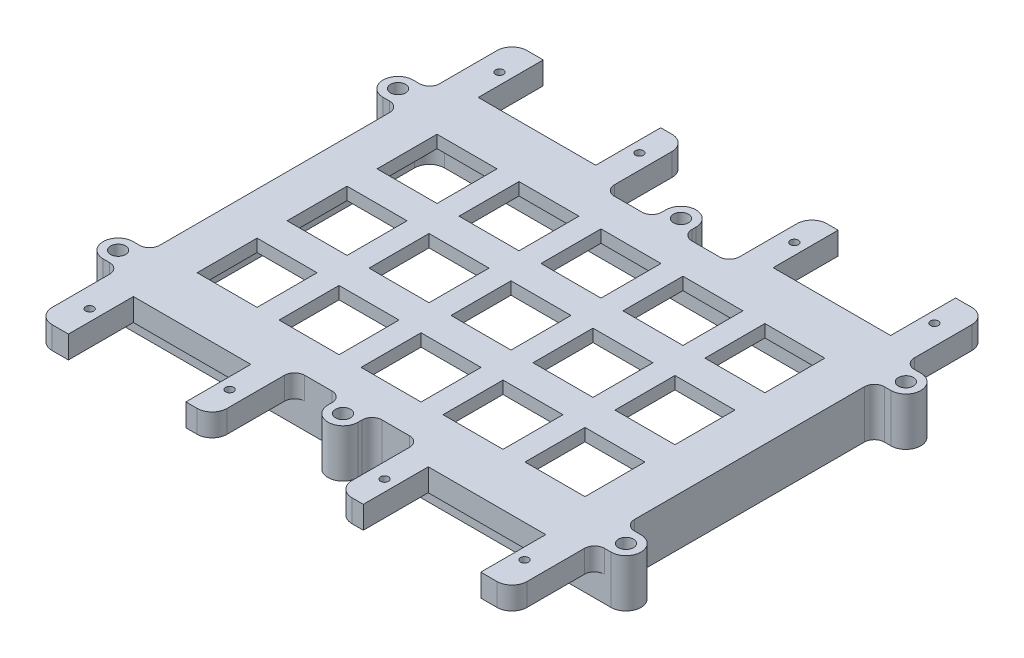
SolidWorks part; units mm, degrees
ref_plane "前视基准面" through (0, 0, 0) normal (0, 0, 1) x (1, 0, 0)
ref_plane "上视基准面" through (0, 0, 0) normal (0, 1, 0) x (1, 0, 0)
ref_plane "右视基准面" through (0, 0, 0) normal (1, 0, 0) x (0, 0, -1)
other "Configuration Table"
sketch "草图1" plane through (0, 0, 0) normal (0, 1, 0) x (1, 0, 0)
  line L0 (0, 35.4779) -> (0, -35.3561) construction
  line L2 (-47.5, 23) -> (-47.5, -23)
  line L4 (47.5, 23) -> (47.5, -23)
  line L5 (-47.5, 31) -> (47.5, -31) construction
  line L6 (-47.5, -31) -> (47.5, 31) construction
  line L15 (-78.7463, 0) -> (58.6748, 0) construction
  line L24 (-10.5, 31) -> (-5, 31)
  line L27 (-10.5, -31) -> (-5, -31)
  line L28 (49.5, 31) -> (50.8, 31)
  line L29 (-49.5, 31) -> (-50.8, 31)
  line L31 (-49.5, 25) -> (-50.8, 25)
  line L33 (49.5, 25) -> (50.8, 25)
  line L36 (49.5, -25) -> (50.8, -25)
  line L37 (49.5, -31) -> (50.8, -31)
  line L38 (-49.5, -31) -> (-50.8, -31)
  line L39 (-49.5, -25) -> (-50.8, -25)
  line L41 (-3, -33.8) -> (-3, -33)
  line L43 (-3, 33.8) -> (-3, 33)
  line L45 (3, 33.8) -> (3, 33)
  line L47 (3, -33.8) -> (3, -33)
  line L48 (5, 31) -> (10.5, 31)
  line L49 (5, -31) -> (10.5, -31)
  line L54 (29.5, 63.8424) -> (29.5, 47.5) construction
  line L56 (47.5, 33) -> (47.5, 44.5)
  line L57 (44.5, 47.5) -> (41.25, 47.5)
  line L58 (12.5, 33) -> (12.5, 44.5)
  line L59 (17.75, 47.5) -> (15.5, 47.5)
  line L60 (17.75, 34.5) -> (41.25, 34.5)
  line L61 (17.75, 34.5) -> (17.75, 47.5)
  line L63 (41.25, 34.5) -> (41.25, 47.5)
  line L65 (12.5, -33) -> (12.5, -44.5)
  line L66 (29.5, 34.5) -> (29.5, 25) construction
  line L67 (17.75, -47.5) -> (15.5, -47.5)
  line L68 (17.75, -34.5) -> (17.75, -47.5)
  line L69 (17.75, -34.5) -> (41.25, -34.5)
  line L70 (41.25, -34.5) -> (41.25, -47.5)
  line L71 (44.5, -47.5) -> (41.25, -47.5)
  line L72 (47.5, -33) -> (47.5, -44.5)
  line L73 (-47.5, -33) -> (-47.5, -44.5)
  line L74 (-44.5, -47.5) -> (-41.25, -47.5)
  line L75 (-41.25, -34.5) -> (-41.25, -47.5)
  line L76 (-17.75, -34.5) -> (-41.25, -34.5)
  line L77 (-17.75, -34.5) -> (-17.75, -47.5)
  line L78 (-17.75, -47.5) -> (-15.5, -47.5)
  line L79 (-12.5, -33) -> (-12.5, -44.5)
  line L82 (-12.5, 33) -> (-12.5, 44.5)
  line L83 (-17.75, 47.5) -> (-15.5, 47.5)
  line L84 (-17.75, 34.5) -> (-17.75, 47.5)
  line L85 (-17.75, 34.5) -> (-41.25, 34.5)
  line L86 (-41.25, 34.5) -> (-41.25, 47.5)
  line L87 (-44.5, 47.5) -> (-41.25, 47.5)
  line L88 (-47.5, 33) -> (-47.5, 44.5)
  arc A4 (-50.8, 31) -> (-50.8, 25) centre (-50.8, 28) ccw
  circle A5 centre (-50.8, 28) radius 1.5
  circle A6 centre (50.8, 28) radius 1.5
  arc A7 (50.8, 31) -> (50.8, 25) centre (50.8, 28) cw
  circle A8 centre (50.8, -28) radius 1.5
  arc A9 (50.8, -31) -> (50.8, -25) centre (50.8, -28) ccw
  circle A10 centre (-50.8, -28) radius 1.5
  arc A11 (-50.8, -31) -> (-50.8, -25) centre (-50.8, -28) cw
  arc A12 (-3, 33.8) -> (3, 33.8) centre (0, 33.8) cw
  circle A13 centre (0, 33.8) radius 1.5
  circle A14 centre (0, -33.8) radius 1.5
  arc A15 (-3, -33.8) -> (3, -33.8) centre (0, -33.8) ccw
  arc A16 (47.5, 44.5) -> (44.5, 47.5) centre (44.5, 44.5) ccw
  arc A17 (15.5, 47.5) -> (12.5, 44.5) centre (15.5, 44.5) ccw
  circle A18 centre (43.5, 41) radius 0.8
  circle A19 centre (15.5, 41) radius 0.8
  circle A20 centre (43.5, -41) radius 0.8
  circle A21 centre (15.5, -41) radius 0.8
  arc A22 (15.5, -47.5) -> (12.5, -44.5) centre (15.5, -44.5) cw
  arc A23 (47.5, -44.5) -> (44.5, -47.5) centre (44.5, -44.5) cw
  circle A24 centre (-15.5, -41) radius 0.8
  circle A25 centre (-43.5, -41) radius 0.8
  arc A26 (-47.5, -44.5) -> (-44.5, -47.5) centre (-44.5, -44.5) ccw
  arc A27 (-15.5, -47.5) -> (-12.5, -44.5) centre (-15.5, -44.5) ccw
  circle A28 centre (-43.5, 41) radius 0.8
  circle A29 centre (-15.5, 41) radius 0.8
  arc A30 (-15.5, 47.5) -> (-12.5, 44.5) centre (-15.5, 44.5) cw
  arc A31 (-47.5, 44.5) -> (-44.5, 47.5) centre (-44.5, 44.5) cw
  arc A32 (47.5, -23) -> (49.5, -25) centre (49.5, -23) ccw
  arc A33 (49.5, 25) -> (47.5, 23) centre (49.5, 23) ccw
  arc A34 (-49.5, -25) -> (-47.5, -23) centre (-49.5, -23) ccw
  arc A35 (-47.5, 23) -> (-49.5, 25) centre (-49.5, 23) ccw
  arc A36 (-49.5, -31) -> (-47.5, -33) centre (-49.5, -33) cw
  arc A37 (-12.5, -33) -> (-10.5, -31) centre (-10.5, -33) cw
  arc A38 (-3, -33) -> (-5, -31) centre (-5, -33) ccw
  arc A39 (5, -31) -> (3, -33) centre (5, -33) ccw
  arc A40 (10.5, -31) -> (12.5, -33) centre (10.5, -33) cw
  arc A41 (47.5, -33) -> (49.5, -31) centre (49.5, -33) cw
  arc A42 (47.5, 33) -> (49.5, 31) centre (49.5, 33) ccw
  arc A43 (10.5, 31) -> (12.5, 33) centre (10.5, 33) ccw
  arc A44 (5, 31) -> (3, 33) centre (5, 33) cw
  arc A45 (-3, 33) -> (-5, 31) centre (-5, 33) cw
  arc A46 (-10.5, 31) -> (-12.5, 33) centre (-10.5, 33) cw
  arc A47 (-47.5, 33) -> (-49.5, 31) centre (-49.5, 33) cw
  point P0 (0, 0)
  point P14 (47.5, -25)
  point P21 (29.5, 41)
  point P24 (47.5, 25)
  point P62 (47.5, 47.5)
  point P65 (12.5, 47.5)
  point P117 (-47.5, -25)
  point P120 (-47.5, 25)
  point P126 (-12.5, -31)
  point P129 (-3, -31)
  point P132 (3, -31)
  point P135 (12.5, -31)
  point P144 (12.5, 31)
  point P147 (3, 31)
  point P150 (-3, 31)
  point P153 (-12.5, 31)
  dimension "D8" = 2.8
  dimension "D11" = 3
  dimension "D12" = 6.5
  dimension "D3" = 2
  dimension "D1" = 95
  dimension "D2" = 62
  dimension "D4" = 35
  dimension "D5" = 23.5
  dimension "D6" = 3.3
  dimension "D7" = 6
  dimension "D9" = 6
  dimension "D13" = 2.25
extrude "凸台-拉伸1" add sketch "草图1" against normal blind 9.6
sketch "草图2" plane through (0, -9.6, 0) normal (0, -1, 0) x (1, 0, 0)
  line L0 (-63.1336, 0) -> (63.5579, 0) construction
  line L5 (0, 56.9992) -> (0, 48.5806) construction
  line L18 (3, 33.8) -> (3, 33) construction
  line L19 (63.5579, 31) -> (5, 31)
  line L20 (63.5579, 31) -> (63.5579, 53.6942)
  line L21 (63.5579, 53.6942) -> (-73.0103, 53.6942)
  line L22 (-73.0103, 31) -> (-73.0103, 53.6942)
  line L23 (-3, 33) -> (-3, 33.8) construction
  line L24 (3, 33.8) -> (3, 33)
  line L25 (-3, 33) -> (-3, 33.8)
  line L26 (-5, 31) -> (-73.0103, 31)
  line L27 (63.5579, -31) -> (63.5579, -53.6942)
  line L28 (63.5579, -53.6942) -> (-73.0103, -53.6942)
  line L29 (-73.0103, -31) -> (-73.0103, -53.6942)
  line L30 (-5, -31) -> (-73.0103, -31)
  line L31 (-3, -33) -> (-3, -33.8)
  line L32 (3, -33.8) -> (3, -33)
  line L33 (63.5579, -31) -> (5, -31)
  arc A3 (3, 33) -> (5, 31) centre (5, 33) ccw construction
  arc A4 (3, 33.8) -> (-3, 33.8) centre (0, 33.8) ccw construction
  arc A5 (-5, 31) -> (-3, 33) centre (-5, 33) ccw construction
  arc A6 (3, 33) -> (5, 31) centre (5, 33) ccw
  arc A7 (3, 33.8) -> (-3, 33.8) centre (0, 33.8) ccw
  arc A8 (-5, 31) -> (-3, 33) centre (-5, 33) ccw
  arc A9 (-5, -31) -> (-3, -33) centre (-5, -33) cw
  arc A10 (3, -33.8) -> (-3, -33.8) centre (0, -33.8) cw
  arc A11 (3, -33) -> (5, -31) centre (5, -33) cw
extrude "切除-拉伸1" cut sketch "草图2" against normal blind 5.1
sketch "草图3" plane through (0, -9.6, 0) normal (0, -1, 0) x (1, 0, 0)
  line L0 (47.5, 23) -> (47.5, -23) construction
  line L1 (-45, -28.5) -> (45, -28.5)
  line L2 (-45, -28.5) -> (-45, 28.5)
  line L3 (-45, 28.5) -> (45, 28.5)
  line L4 (45, -28.5) -> (45, 28.5)
  line L5 (-45, -28.5) -> (45, 28.5) construction
  line L6 (-45, 28.5) -> (45, -28.5) construction
  line L7 (-50.8, 31) -> (-5, 31) construction
  point P0 (0, 0)
  dimension "D1" = 2.5
  dimension "D2" = 2.5
extrude "切除-拉伸2" cut sketch "草图3" against normal blind 7.1
fillet "圆角1" radius 3 4 edges at (-45, -6.05, -28.5) (-45, -6.05, 28.5) (45, -6.05, -28.5) (45, -6.05, 28.5)
sketch "草图11" plane through (0, -2.5, 0) normal (0, -1, 0) x (1, 0, 0)
  line L0 (0, 44.5522) -> (0, -50.2123) construction
  line L1 (-64.7486, 0) -> (58.5739, 0) construction
  line L2 (42, 28.5) -> (-42, 28.5) construction
  line L3 (-30, 17) -> (30, 17)
  line L4 (-30, 17) -> (-30, 19.5)
  line L5 (-30, 19.5) -> (-1.5, 19.5)
  line L6 (30, 17) -> (30, 19.5)
  line L7 (-30, 17) -> (30, 19.5) construction
  line L8 (-30, 19.5) -> (30, 17) construction
  line L9 (1.5, 19.5) -> (30, 19.5)
  line L10 (-1.5, 28.5) -> (1.5, 28.5)
  line L11 (-1.5, 28.5) -> (-1.5, 19.5)
  line L13 (1.5, 28.5) -> (1.5, 19.5)
  line L14 (1.5, -28.5) -> (1.5, -19.5)
  line L15 (-1.5, -28.5) -> (1.5, -28.5)
  line L16 (-1.5, -28.5) -> (-1.5, -19.5)
  line L17 (-30, -19.5) -> (-1.5, -19.5)
  line L18 (-30, -17) -> (-30, -19.5)
  line L19 (-30, -17) -> (30, -17)
  line L20 (30, -17) -> (30, -19.5)
  line L21 (1.5, -19.5) -> (30, -19.5)
  point P5 (0, 18.25)
  dimension "D1" = 60
  dimension "D2" = 2.5
  dimension "D3" = 9
  dimension "D4" = 3
extrude "凸台-拉伸2" [suppressed] add sketch "草图11" along normal blind 2
sketch "草图12" plane through (0, -2.5, 0) normal (0, -1, 0) x (1, 0, 0)
  line L0 (0, 44.2091) -> (0, -42.6655) construction
  line L1 (-42, 25.5) -> (-7, 25.5)
  line L2 (-42, 25.5) -> (-42, 23)
  line L3 (-42, 23) -> (-7, 23)
  line L4 (-7, 25.5) -> (-7, 23)
  line L5 (-53.0853, 0) -> (71.5236, 0) construction
  line L6 (42, 23) -> (7, 23)
  line L7 (7, 25.5) -> (7, 23)
  line L8 (42, 25.5) -> (7, 25.5)
  line L9 (42, 25.5) -> (42, 23)
  line L10 (42, -25.5) -> (42, -23)
  line L11 (42, -25.5) -> (7, -25.5)
  line L12 (7, -25.5) -> (7, -23)
  line L13 (42, -23) -> (7, -23)
  line L14 (-42, -23) -> (-7, -23)
  line L15 (-7, -25.5) -> (-7, -23)
  line L16 (-42, -25.5) -> (-7, -25.5)
  line L17 (-42, -25.5) -> (-42, -23)
  dimension "D1" = 35
  dimension "D2" = 2.5
fillet "圆角2" radius 1 8 edges at (0, -2.5, -28.5) (-44.1213, -2.5, -27.6213) (-45, -2.5, 0) (-44.1213, -2.5, 27.6213) (0, -2.5, 28.5) (44.1213, -2.5, 27.6213) (45, -2.5, 0) (44.1213, -2.5, -27.6213)
sketch "草图13" plane through (0, -2.5, 0) normal (0, -1, 0) x (1, 0, 0)
  line L0 (-56.0869, 0) -> (61.3182, 0) construction
  line L1 (0, 42.7512) -> (0, -42.4082) construction
  line L2 (-45, -25.5) -> (-45, 25.5) construction
  line L3 (-39, 24) -> (-27, 24)
  line L4 (-39, 24) -> (-39, 12)
  line L5 (-39, 12) -> (-27, 12)
  line L6 (-27, 24) -> (-27, 12)
  line L7 (-39, 24) -> (-27, 12) construction
  line L8 (-39, 12) -> (-27, 24) construction
  line L9 (-22.6, 24) -> (-22.6, 12)
  line L10 (-22.6, 24) -> (-10.6, 24)
  line L11 (-10.6, 24) -> (-10.6, 12)
  line L12 (-22.6, 12) -> (-10.6, 12)
  line L13 (-6.2, 24) -> (-6.2, 12)
  line L14 (-6.2, 24) -> (5.8, 24)
  line L15 (5.8, 24) -> (5.8, 12)
  line L16 (-6.2, 12) -> (5.8, 12)
  line L17 (10.2, 24) -> (10.2, 12)
  line L18 (10.2, 24) -> (22.2, 24)
  line L19 (22.2, 24) -> (22.2, 12)
  line L20 (10.2, 12) -> (22.2, 12)
  line L21 (26.6, 24) -> (26.6, 12)
  line L22 (26.6, 24) -> (38.6, 24)
  line L23 (38.6, 24) -> (38.6, 12)
  line L24 (26.6, 12) -> (38.6, 12)
  line L25 (-22.6, 6) -> (-22.6, -6)
  line L26 (-22.6, 6) -> (-10.6, 6)
  line L27 (-10.6, 6) -> (-10.6, -6)
  line L28 (-22.6, -6) -> (-10.6, -6)
  line L29 (-6.2, 6) -> (-6.2, -6)
  line L30 (-6.2, 6) -> (5.8, 6)
  line L31 (5.8, 6) -> (5.8, -6)
  line L32 (-6.2, -6) -> (5.8, -6)
  line L33 (10.2, 6) -> (10.2, -6)
  line L34 (10.2, 6) -> (22.2, 6)
  line L35 (22.2, 6) -> (22.2, -6)
  line L36 (10.2, -6) -> (22.2, -6)
  line L37 (26.6, 6) -> (26.6, -6)
  line L38 (26.6, 6) -> (38.6, 6)
  line L39 (38.6, 6) -> (38.6, -6)
  line L40 (26.6, -6) -> (38.6, -6)
  line L41 (-22.6, -12) -> (-22.6, -24)
  line L42 (-22.6, -12) -> (-10.6, -12)
  line L43 (-10.6, -12) -> (-10.6, -24)
  line L44 (-22.6, -24) -> (-10.6, -24)
  line L45 (-6.2, -12) -> (-6.2, -24)
  line L46 (-6.2, -12) -> (5.8, -12)
  line L47 (5.8, -12) -> (5.8, -24)
  line L48 (-6.2, -24) -> (5.8, -24)
  line L49 (10.2, -12) -> (10.2, -24)
  line L50 (10.2, -12) -> (22.2, -12)
  line L51 (22.2, -12) -> (22.2, -24)
  line L52 (10.2, -24) -> (22.2, -24)
  line L53 (26.6, -12) -> (26.6, -24)
  line L54 (26.6, -12) -> (38.6, -12)
  line L55 (38.6, -12) -> (38.6, -24)
  line L56 (26.6, -24) -> (38.6, -24)
  line L57 (-39, 6) -> (-39, -6)
  line L58 (-39, 6) -> (-27, 6)
  line L59 (-27, 6) -> (-27, -6)
  line L60 (-39, -6) -> (-27, -6)
  line L61 (-39, -12) -> (-39, -24)
  line L62 (-39, -12) -> (-27, -12)
  line L63 (-27, -12) -> (-27, -24)
  line L64 (-39, -24) -> (-27, -24)
  point P5 (-33, 18)
  dimension "D1" = 12
  dimension "D2" = 12
  dimension "D3" = 18
  dimension "D4" = 12
  dimension "D5" = 5
  dimension "D6" = 3
extrude "切除-拉伸3" cut sketch "草图13" against normal through all
sketch "草图14" plane through (0, 0, 0) normal (0, 1, 0) x (1, 0, 0)
  line L0 (-68.0075, 0) -> (71.0091, 0) construction
  line L1 (-63.4622, 0) -> (-63.4622, 7.2467) construction
  line L2 (-63.4622, 7.2467) -> (-64.4137, 18.0106) construction
  line L3 (-64.4137, 18.0106) -> (-59.4315, 38.3775) construction
  line L4 (-59.4315, 38.3775) -> (-52.1419, 42.494) construction
  line L5 (-52.1419, 42.494) -> (-26.4998, 43.6088) construction
  line L7 (-26.4998, 43.6088) -> (-4.5453, 44.0376) construction
  line L8 (-4.5453, 44.0376) -> (11.9206, 43.3516) construction
  line L11 (11.9206, 43.3516) -> (26.4998, 42.1509) construction
  line L14 (26.4998, 42.1509) -> (44.9381, 38.1202) construction
  line L15 (44.9381, 38.1202) -> (56.8222, 32.2807) construction
  line L18 (56.8222, 32.2807) -> (65.2266, 16.5866) construction
  line L19 (65.2266, 16.5866) -> (66.1208, 8.2758) construction
  line L20 (66.1208, 8.2758) -> (65.6062, 0) construction
  line L21 (-63.4622, 0) -> (-63.4622, -7.2467) construction
  line L22 (-63.4622, -7.2467) -> (-64.4137, -18.0106) construction
  line L23 (-64.4137, -18.0106) -> (-59.4315, -38.3775) construction
  line L24 (-59.4315, -38.3775) -> (-52.1419, -42.494) construction
  line L25 (-52.1419, -42.494) -> (-26.4998, -43.6088) construction
  line L26 (-26.4998, -43.6088) -> (-4.5453, -44.0376) construction
  line L27 (-4.5453, -44.0376) -> (11.9206, -43.3516) construction
  line L28 (11.9206, -43.3516) -> (26.4998, -42.1509) construction
  line L29 (26.4998, -42.1509) -> (44.9381, -38.1202) construction
  line L30 (44.9381, -38.1202) -> (56.8222, -32.2807) construction
  line L31 (56.8222, -32.2807) -> (65.2266, -16.5866) construction
  line L32 (65.2266, -16.5866) -> (66.1208, -8.2758) construction
  line L33 (66.1208, -8.2758) -> (65.6062, 0) construction
  spline_without_curve S0
  spline_without_curve S1
  point P9 (-59.26, 31.0879)
  point P10 (-52.3134, 36.7481)
  point P13 (-62.5189, 37.1768)
  point P14 (-51.9704, 39.4066)
  point P15 (-38.5919, 42.494)
  point P16 (-14.4076, 43.6946)
  point P17 (2.144, 43.2658)
  point P18 (-59.4315, 38.3775)
  point P20 (-30.0159, 44.1234)
  point P21 (-4.5453, 44.0376)
  point P22 (0, 0)
  point P23 (-52.1419, 42.494)
  point P24 (-26.4998, 43.6088)
  point P25 (11.9206, 43.3516)
  point P28 (26.4998, 42.1509)
  point P29 (46.053, 38.2917)
  point P30 (66.1208, 8.2758)
  point P31 (44.9381, 38.1202)
ref_plane "基准面1" through (0, 16, 0) normal (0, 1, 0) x (1, 0, 0)
sketch "草图15" plane through (0, 16, 0) normal (0, 1, 0) x (1, 0, 0)
  spline S0 degree 13 poles (-1197.7348, 1646.0463) (1331.2327, -1681.7529) (-1659.9912, 1377.5662) (1581.9207, -743.3804) (-1458.2782, 202.7577) (764.0136, -59.6805) (-441.1806, -149.9595) (446.5338, 146.9669) (-590.8409, -338.3898) (949.5195, 410.8367) (-861.06, -746.3949) (998.2363, 1236.893) (-874.6396, -1597.7248) (951.1452, 1792.5914) knots -0.353239 -0.353239 -0.353239 -0.353239 -0.353239 -0.353239 -0.353239 -0.353239 -0.353239 -0.353239 -0.353239 -0.353239 -0.353239 -0.353239 1.376775 1.376775 1.376775 1.376775 1.376775 1.376775 1.376775 1.376775 1.376775 1.376775 1.376775 1.376775 1.376775 1.376775 only from (-63.4622, 0) to (65.6062, 0) construction
  spline S1 degree 13 poles (-1197.7348, -1646.0463) (1331.2327, 1681.7529) (-1659.9912, -1377.5662) (1581.9207, 743.3804) (-1458.2782, -202.7577) (764.0136, 59.6805) (-441.1806, 149.9595) (446.5338, -146.9669) (-590.8409, 338.3898) (949.5195, -410.8367) (-861.06, 746.3949) (998.2363, -1236.893) (-874.6396, 1597.7248) (951.1452, -1792.5914) knots -0.353239 -0.353239 -0.353239 -0.353239 -0.353239 -0.353239 -0.353239 -0.353239 -0.353239 -0.353239 -0.353239 -0.353239 -0.353239 -0.353239 1.376775 1.376775 1.376775 1.376775 1.376775 1.376775 1.376775 1.376775 1.376775 1.376775 1.376775 1.376775 1.376775 1.376775 only from (-63.4622, 0) to (65.6062, 0) construction
  spline S2 degree 13 poles (-63.4622, 0) (-63.4622, -7.2467) (-64.4137, -18.0106) (-59.4315, -38.3775) (-52.1419, -42.494) (-26.4998, -43.6088) (-4.5453, -44.0376) (11.9206, -43.3516) (26.4998, -42.1509) (44.9381, -38.1202) (56.8222, -32.2807) (65.2266, -16.5866) (66.1208, -8.2758) (65.6062, 0) knots 0 0 0 0 0 0 0 0 0 0 0 0 0 0 1 1 1 1 1 1 1 1 1 1 1 1 1 1
  spline S3 degree 13 poles (-63.4622, 0) (-63.4622, 7.2467) (-64.4137, 18.0106) (-59.4315, 38.3775) (-52.1419, 42.494) (-26.4998, 43.6088) (-4.5453, 44.0376) (11.9206, 43.3516) (26.4998, 42.1509) (44.9381, 38.1202) (56.8222, 32.2807) (65.2266, 16.5866) (66.1208, 8.2758) (65.6062, 0) knots 0 0 0 0 0 0 0 0 0 0 0 0 0 0 1 1 1 1 1 1 1 1 1 1 1 1 1 1
  spline S4 degree 1 poles (-63.4622, 0) (65.6062, 0) knots 0 0 1 1 construction
  spline S5 degree 3 poles (-63.4622, 0) (-63.4622, -0.2512) (-63.4652, -0.7446) (-63.4762, -1.8026) (-63.487, -3.2182) (-63.4623, -5.0821) (-63.3419, -7.7615) (-62.9635, -11.415) (-61.9733, -16.0218) (-60.3084, -20.5814) (-57.0614, -26.309) (-50.9191, -32.3881) (-40.3797, -37.4421) (-27.5126, -40.4427) (-13.4162, -41.7912) (0.9149, -41.829) (14.7805, -40.7074) (27.747, -38.3811) (39.4852, -34.678) (49.6093, -29.4311) (57.6317, -22.6665) (62.1597, -16.1319) (64.3772, -10.8435) (65.3636, -6.997) (65.7392, -3.3664) (65.6768, -1.1359) (65.6062, 0) knots 0 0 0 0 0.007812 0.015625 0.03125 0.046875 0.0625 0.09375 0.125 0.15625 0.1875 0.25 0.3125 0.375 0.4375 0.5 0.5625 0.625 0.6875 0.75 0.8125 0.875 0.90625 0.9375 0.96875 1 1 1 1
  spline S6 degree 1 poles (-48.4622, 0) (50.5772, 0) knots 0 0 1 1 construction
  spline S7 degree 1 poles (-48.4622, 0) (50.5772, 0) knots 0 0 1 1 construction
  spline S8 degree 3 poles (-48.4622, 0) (-48.4622, -0.2947) (-48.4659, -0.9022) (-48.4772, -1.9729) (-48.486, -3.2287) (-48.4648, -4.6964) (-48.373, -6.673) (-48.1028, -9.1787) (-47.473, -12.0024) (-46.5646, -14.4003) (-45.4222, -16.3534) (-43.9505, -18.0732) (-41.8609, -19.7775) (-38.8693, -21.4859) (-33.56, -23.616) (-24.6589, -25.6724) (-11.9516, -26.824) (1.2447, -26.7891) (13.8626, -25.6806) (25.1884, -23.525) (34.7063, -20.344) (42.0173, -16.3085) (46.9761, -11.8148) (49.3072, -8.1132) (50.1454, -5.8678) (50.439, -4.7249) (50.5813, -3.932) (50.6612, -3.1782) (50.6861, -2.5311) (50.6819, -1.9473) (50.668, -1.535) (50.6521, -1.2192) (50.642, -1.0438) (50.6365, -0.9536) (50.6234, -0.742) (50.6036, -0.4238) (50.586, -0.1413) (50.5772, 0) knots 0 0 0 0 0.00788 0.01576 0.03152 0.047281 0.063041 0.094561 0.126082 0.157602 0.189122 0.220643 0.252163 0.283683 0.315204 0.378245 0.441285 0.504326 0.567367 0.630408 0.693448 0.756489 0.81953 0.882571 0.914091 0.929851 0.945611 0.961372 0.977132 0.985012 0.992892 0.996832 0.998802 0.999787 1.000772 1.004712 1.008652 1.008652 1.008652 1.008652
  spline S9 degree 3 poles (50.5772, 0) (50.586, 0.1413) (50.6036, 0.4238) (50.6234, 0.742) (50.6365, 0.9536) (50.642, 1.0438) (50.6521, 1.2192) (50.668, 1.535) (50.6819, 1.9473) (50.6861, 2.5311) (50.6612, 3.1782) (50.5813, 3.932) (50.439, 4.7249) (50.1454, 5.8678) (49.3072, 8.1132) (46.9761, 11.8148) (42.0173, 16.3085) (34.7063, 20.344) (25.1884, 23.525) (13.8626, 25.6806) (1.2447, 26.7891) (-11.9516, 26.824) (-24.6589, 25.6724) (-33.56, 23.616) (-38.8693, 21.4859) (-41.8609, 19.7775) (-43.9505, 18.0732) (-45.4222, 16.3534) (-46.5646, 14.4003) (-47.473, 12.0024) (-48.1028, 9.1787) (-48.373, 6.673) (-48.4648, 4.6964) (-48.486, 3.2287) (-48.4772, 1.9729) (-48.4659, 0.9022) (-48.4622, 0.2947) (-48.4622, 0) knots 0 0 0 0 0.00394 0.00788 0.008865 0.00985 0.01182 0.01576 0.02364 0.03152 0.047281 0.063041 0.078801 0.094561 0.126082 0.189122 0.252163 0.315204 0.378245 0.441285 0.504326 0.567367 0.630408 0.693448 0.724969 0.756489 0.788009 0.81953 0.85105 0.882571 0.914091 0.945611 0.961372 0.977132 0.992892 1.000772 1.008652 1.008652 1.008652 1.008652
  dimension "D1" = 0
  dimension "D2" = 15
sketch3d "3D草图1"
  line L0 (-48.4622, 16, 0) -> (-58.7197, 15.1011, 0) construction
  line L1 (-12.6856, 16, -26.5887) -> (-11.8879, 15.2687, -36.7131) construction
  line L2 (-58.7197, 15.1011, 0) -> (-61.8146, 9.9937, -0.2516) construction
  line L3 (-61.8146, 9.9937, -0.2516) -> (-63.2774, 5.5626, 0) construction
  line L4 (-63.2774, 5.5626, 0) -> (-63.4622, 0, 0) construction
  line L5 (41.25, 0, -34.5) -> (17.75, 0, -34.5) construction
  line L6 (31.4344, 16, 21.3482) -> (31.4344, 10.5152, 25.6352) construction
  line L7 (31.4344, 10.5152, 25.6352) -> (34.5949, 12.5114, 30.5561) construction
  line L8 (50.5772, 16, 0) -> (55.9129, 12.6846, 0) construction
  line L9 (34.5949, 12.5114, 30.5561) -> (35.4041, 2.4576, 28.4064) construction
  line L10 (55.9129, 12.6846, 0) -> (61.2509, 8.9118, 0) construction
  line L11 (61.2509, 8.9118, 0) -> (59.9583, 5.1693, 0) construction
  line L12 (59.9583, 5.1693, 0) -> (65.6062, 0, 0) construction
  line L13 (35.4041, 2.4576, 28.4064) -> (39.0215, 0, 34.5) construction
  line L17 (-11.8879, 15.2687, -36.7131) -> (-12.3138, 10.6731, -37.9884) construction
  line L20 (-12.3138, 10.6731, -37.9884) -> (-14.8253, 0, -41.4952) construction
  line L21 (-12.6856, 16, 26.5887) -> (-11.8879, 15.2687, 36.7131) construction
  line L23 (-11.8879, 15.2687, 36.7131) -> (-12.3138, 10.6731, 37.9884) construction
  line L24 (-12.3138, 10.6731, 37.9884) -> (-14.8253, 0, 41.4952) construction
  line L29 (31.4344, 16, -21.3482) -> (31.4344, 10.5152, -25.6352) construction
  line L32 (31.4344, 10.5152, -25.6352) -> (34.5949, 12.5114, -30.5561) construction
  line L33 (34.5949, 12.5114, -30.5561) -> (35.4041, 2.4576, -28.4064) construction
  line L34 (35.4041, 2.4576, -28.4064) -> (39.0215, 0, -34.5) construction
  spline S0 degree 3 poles (50.5772, 16, 0) (50.586, 16, -0.1413) (50.6036, 16, -0.4238) (50.6234, 16, -0.742) (50.6365, 16, -0.9536) (50.642, 16, -1.0438) (50.6521, 16, -1.2192) (50.668, 16, -1.535) (50.6819, 16, -1.9473) (50.6861, 16, -2.5311) (50.6612, 16, -3.1782) (50.5813, 16, -3.932) (50.439, 16, -4.7249) (50.1454, 16, -5.8678) (49.3072, 16, -8.1132) (46.9761, 16, -11.8148) (42.0173, 16, -16.3085) (34.7063, 16, -20.344) (25.1884, 16, -23.525) (13.8626, 16, -25.6806) (1.2447, 16, -26.7891) (-11.9516, 16, -26.824) (-24.6589, 16, -25.6724) (-33.56, 16, -23.616) (-38.8693, 16, -21.4859) (-41.8609, 16, -19.7775) (-43.9505, 16, -18.0732) (-45.4222, 16, -16.3534) (-46.5646, 16, -14.4003) (-47.473, 16, -12.0024) (-48.1028, 16, -9.1787) (-48.373, 16, -6.673) (-48.4648, 16, -4.6964) (-48.486, 16, -3.2287) (-48.4772, 16, -1.9729) (-48.4659, 16, -0.9022) (-48.4622, 16, -0.2947) (-48.4622, 16, 0) knots 0 0 0 0 0.00394 0.00788 0.008865 0.00985 0.01182 0.01576 0.02364 0.03152 0.047281 0.063041 0.078801 0.094561 0.126082 0.189122 0.252163 0.315204 0.378245 0.441285 0.504326 0.567367 0.630408 0.693448 0.724969 0.756489 0.788009 0.81953 0.85105 0.882571 0.914091 0.945611 0.961372 0.977132 0.992892 1.000772 1.008652 1.008652 1.008652 1.008652 construction
  spline_without_curve S1
  spline_without_curve S2
  spline_without_curve S3
  spline S4 degree 13 poles (-63.4622, 0, 0) (-63.4622, 0, -7.2467) (-64.4137, 0, -18.0106) (-59.4315, 0, -38.3775) (-52.1419, 0, -42.494) (-26.4998, 0, -43.6088) (-4.5453, 0, -44.0376) (11.9206, 0, -43.3516) (26.4998, 0, -42.1509) (44.9381, 0, -38.1202) (56.8222, 0, -32.2807) (65.2266, 0, -16.5866) (66.1208, 0, -8.2758) (65.6062, 0, 0) knots 0 0 0 0 0 0 0 0 0 0 0 0 0 0 1 1 1 1 1 1 1 1 1 1 1 1 1 1 construction
  spline_without_curve S5
  spline_without_curve S8
  spline_without_curve S9
  point P1 (0, 0, 0)
  point P2 (37.1558, 0, -34.5)
  point P21 (35.4041, 2.4576, -28.4064)
  point P23 (35.0984, 9.039, -24.5251)
  point P24 (34.5949, 12.5114, -30.5561)
sketch "草图16" plane through (0, 16, 0) normal (0, 1, 0) x (1, 0, 0)
  spline S0 degree 3 poles (-158.1064, -1996.766) (-49.1654, 56.7698) (-48.3475, 10.3116) (-48.4772, -1.9729) (-48.486, -3.2287) (-48.4648, -4.6964) (-48.373, -6.673) (-48.1028, -9.1787) (-47.473, -12.0024) (-46.5646, -14.4003) (-45.4222, -16.3534) (-43.9505, -18.0732) (-41.8609, -19.7775) (-38.8693, -21.4859) (-33.56, -23.616) (-24.6589, -25.6724) (-11.9516, -26.824) (1.2447, -26.7891) (13.8626, -25.6806) (25.1884, -23.525) (34.7063, -20.344) (42.0173, -16.3085) (46.9761, -11.8148) (49.3072, -8.1132) (50.1454, -5.8678) (50.439, -4.7249) (50.5813, -3.932) (50.6612, -3.1782) (50.6861, -2.5311) (50.6819, -1.9473) (50.668, -1.535) (50.6521, -1.2192) (50.642, -1.0438) (50.6365, -0.9536) (50.6234, -0.742) (48.5132, 33.2469) (46.2392, 61.8174) (102.8259, 1999.2267) knots -0.330107 -0.330107 -0.330107 -0.330107 0.00788 0.01576 0.03152 0.047281 0.063041 0.094561 0.126082 0.157602 0.189122 0.220643 0.252163 0.283683 0.315204 0.378245 0.441285 0.504326 0.567367 0.630408 0.693448 0.756489 0.81953 0.882571 0.914091 0.929851 0.945611 0.961372 0.977132 0.985012 0.992892 0.996832 0.998802 0.999787 1.000772 1.004712 1.946623 1.946623 1.946623 1.946623 only from (-48.4622, 0) to (50.5772, 0) construction
  spline S1 degree 3 poles (102.8255, -1999.214) (46.2393, -61.8173) (48.5132, -33.2469) (50.6234, 0.742) (50.6365, 0.9536) (50.642, 1.0438) (50.6521, 1.2192) (50.668, 1.535) (50.6819, 1.9473) (50.6861, 2.5311) (50.6612, 3.1782) (50.5813, 3.932) (50.439, 4.7249) (50.1454, 5.8678) (49.3072, 8.1132) (46.9761, 11.8148) (42.0173, 16.3085) (34.7063, 20.344) (25.1884, 23.525) (13.8626, 25.6806) (1.2447, 26.7891) (-11.9516, 26.824) (-24.6589, 25.6724) (-33.56, 23.616) (-38.8693, 21.4859) (-41.8609, 19.7775) (-43.9505, 18.0732) (-45.4222, 16.3534) (-46.5646, 14.4003) (-47.473, 12.0024) (-48.1028, 9.1787) (-48.373, 6.673) (-48.4648, 4.6964) (-48.486, 3.2287) (-48.4772, 1.9729) (-48.3475, -10.3117) (-49.1654, -56.7706) (-158.1091, 1996.8178) knots -0.937969 -0.937969 -0.937969 -0.937969 0.00394 0.00788 0.008865 0.00985 0.01182 0.01576 0.02364 0.03152 0.047281 0.063041 0.078801 0.094561 0.126082 0.189122 0.252163 0.315204 0.378245 0.441285 0.504326 0.567367 0.630408 0.693448 0.724969 0.756489 0.788009 0.81953 0.85105 0.882571 0.914091 0.945611 0.961372 0.977132 0.992892 1.000772 1.338762 1.338762 1.338762 1.338762 only from (50.5772, 0) to (-48.4622, 0) construction
  spline S2 degree 3 poles (-48.4622, 0) (-48.4622, -0.2947) (-48.4659, -0.9022) (-48.4772, -1.9729) (-48.486, -3.2287) (-48.4648, -4.6964) (-48.373, -6.673) (-48.1028, -9.1787) (-47.473, -12.0024) (-46.5646, -14.4003) (-45.4222, -16.3534) (-43.9505, -18.0732) (-41.8609, -19.7775) (-38.8693, -21.4859) (-33.56, -23.616) (-24.6589, -25.6724) (-11.9516, -26.824) (1.2447, -26.7891) (13.8626, -25.6806) (25.1884, -23.525) (34.7063, -20.344) (42.0173, -16.3085) (46.9761, -11.8148) (49.3072, -8.1132) (50.1454, -5.8678) (50.439, -4.7249) (50.5813, -3.932) (50.6612, -3.1782) (50.6861, -2.5311) (50.6819, -1.9473) (50.668, -1.535) (50.6521, -1.2192) (50.642, -1.0438) (50.6365, -0.9536) (50.6234, -0.742) (50.6036, -0.4238) (50.586, -0.1413) (50.5772, 0) knots 0 0 0 0 0.00788 0.01576 0.03152 0.047281 0.063041 0.094561 0.126082 0.157602 0.189122 0.220643 0.252163 0.283683 0.315204 0.378245 0.441285 0.504326 0.567367 0.630408 0.693448 0.756489 0.81953 0.882571 0.914091 0.929851 0.945611 0.961372 0.977132 0.985012 0.992892 0.996832 0.998802 0.999787 1.000772 1.004712 1.008652 1.008652 1.008652 1.008652
  spline S3 degree 3 poles (50.5772, 0) (50.586, 0.1413) (50.6036, 0.4238) (50.6234, 0.742) (50.6365, 0.9536) (50.642, 1.0438) (50.6521, 1.2192) (50.668, 1.535) (50.6819, 1.9473) (50.6861, 2.5311) (50.6612, 3.1782) (50.5813, 3.932) (50.439, 4.7249) (50.1454, 5.8678) (49.3072, 8.1132) (46.9761, 11.8148) (42.0173, 16.3085) (34.7063, 20.344) (25.1884, 23.525) (13.8626, 25.6806) (1.2447, 26.7891) (-11.9516, 26.824) (-24.6589, 25.6724) (-33.56, 23.616) (-38.8693, 21.4859) (-41.8609, 19.7775) (-43.9505, 18.0732) (-45.4222, 16.3534) (-46.5646, 14.4003) (-47.473, 12.0024) (-48.1028, 9.1787) (-48.373, 6.673) (-48.4648, 4.6964) (-48.486, 3.2287) (-48.4772, 1.9729) (-48.4659, 0.9022) (-48.4622, 0.2947) (-48.4622, 0) knots 0 0 0 0 0.00394 0.00788 0.008865 0.00985 0.01182 0.01576 0.02364 0.03152 0.047281 0.063041 0.078801 0.094561 0.126082 0.189122 0.252163 0.315204 0.378245 0.441285 0.504326 0.567367 0.630408 0.693448 0.724969 0.756489 0.788009 0.81953 0.85105 0.882571 0.914091 0.945611 0.961372 0.977132 0.992892 1.000772 1.008652 1.008652 1.008652 1.008652
  spline S4 degree 1 poles (-43.4622, 0) (45.5676, 0) knots 0 0 1 1 construction
  spline S5 degree 1 poles (45.5676, 0) (-43.4622, 0) knots 0 0 1 1 construction
  spline S6 degree 3 poles (-43.4622, 0) (-43.4622, -0.3092) (-43.4661, -0.9545) (-43.4747, -1.7607) (-43.4808, -2.5104) (-43.4823, -3.452) (-43.4657, -4.5627) (-43.4045, -5.8643) (-43.291, -7.1466) (-43.0677, -8.7833) (-42.6474, -10.6331) (-42.0013, -12.2984) (-41.307, -13.4613) (-40.452, -14.4612) (-39.04, -15.6238) (-36.6681, -16.9803) (-32.0654, -18.8218) (-23.7431, -20.744) (-11.5007, -21.8321) (1.3174, -21.7762) (13.5055, -20.6761) (24.2607, -18.5876) (33.0052, -15.6042) (38.2929, -12.6155) (41.316, -10.1796) (43.0316, -8.4014) (44.2566, -6.7229) (45.0515, -5.2346) (45.4098, -4.2233) (45.567, -3.5745) (45.6368, -3.1534) (45.6684, -2.8184) (45.6815, -2.5203) (45.6847, -2.2539) (45.6804, -1.989) (45.6709, -1.7271) (45.6629, -1.5557) (45.6533, -1.3833) (45.6475, -1.2837) (45.6335, -1.0611) (45.6074, -0.6394) (45.5852, -0.2833) (45.5676, 0) knots 0 0 0 0 0.007903 0.015805 0.023708 0.031611 0.047416 0.063221 0.079026 0.094832 0.126442 0.158053 0.189663 0.221274 0.252884 0.284495 0.316105 0.379326 0.442547 0.505768 0.568989 0.63221 0.695431 0.758652 0.790263 0.821873 0.853484 0.885094 0.916705 0.93251 0.948315 0.96412 0.972023 0.979926 0.987828 0.99178 0.995731 0.997707 0.999682 1.001658 1.003634 1.011536 1.011536 1.011536 1.011536
  spline S7 degree 3 poles (45.5676, 0) (45.5852, 0.2833) (45.6074, 0.6394) (45.6335, 1.0611) (45.6475, 1.2837) (45.6533, 1.3833) (45.6629, 1.5557) (45.6709, 1.7271) (45.6804, 1.989) (45.6847, 2.2539) (45.6815, 2.5203) (45.6684, 2.8184) (45.6368, 3.1534) (45.567, 3.5745) (45.4098, 4.2233) (45.0515, 5.2346) (44.2566, 6.7229) (43.0316, 8.4014) (41.316, 10.1796) (38.2929, 12.6155) (33.0052, 15.6042) (24.2607, 18.5876) (13.5055, 20.6761) (1.3174, 21.7762) (-11.5007, 21.8321) (-23.7431, 20.744) (-32.0654, 18.8218) (-36.6681, 16.9803) (-39.04, 15.6238) (-40.452, 14.4612) (-41.307, 13.4613) (-42.0013, 12.2984) (-42.6474, 10.6331) (-43.0677, 8.7833) (-43.291, 7.1466) (-43.4045, 5.8643) (-43.4657, 4.5627) (-43.4823, 3.452) (-43.4808, 2.5104) (-43.4747, 1.7607) (-43.4661, 0.9545) (-43.4622, 0.3092) (-43.4622, 0) knots -0.002884 -0.002884 -0.002884 -0.002884 0.005019 0.006994 0.00897 0.010946 0.012921 0.016873 0.020824 0.028726 0.036629 0.044532 0.060337 0.076142 0.091947 0.123558 0.155168 0.186779 0.218389 0.25 0.313221 0.376442 0.439663 0.502884 0.566105 0.629326 0.692547 0.724158 0.755768 0.787379 0.818989 0.8506 0.88221 0.913821 0.929626 0.945431 0.961236 0.977042 0.984944 0.992847 1.00075 1.008652 1.008652 1.008652 1.008652
  dimension "D1" = 5
sketch "草图18" plane through (0, 0, 0) normal (0, 1, 0) x (1, 0, 0)
  line L0 (43.5, 28) -> (43.5, -28)
  line L1 (43.5, 28) -> (-50.8, 28)
  line L3 (43.5, -28) -> (-50.8, -28)
  line L4 (-50.8, 28) -> (-50.8, -28)
  line L5 (43.5, 23.9764) -> (-50.8, -28) construction
  line L6 (50.8, -28) -> (-50.8, 28) construction
  point P0 (0, 0)
sketch3d "3D草图3"
  line L0 (-43.4622, 16, 0) -> (-49.2337, 12.2478, 0) construction
  line L1 (-49.2337, 12.2478, 0) -> (-59.0955, 10.6195, 0) construction
  line L2 (-59.0955, 10.6195, 0) -> (-59.6785, 6.9032, 0) construction
  line L3 (45.5676, 16, 0) -> (48.6331, 13.2583, 0) construction
  line L5 (-59.6785, 6.9032, 0) -> (-61.6085, 2.2031, 0) construction
  line L7 (48.6331, 13.2583, 0) -> (55.6092, 5.9653, 0) construction
  line L9 (55.6092, 5.9653, 0) -> (50.2354, 0.866, 0) construction
  line L10 (50.2354, 0.866, 0) -> (43.5, 0, 0) construction
  line L11 (-61.6085, 2.2031, 0) -> (-50.8, 0, 0) construction
  line L12 (43.5, 0, -28) -> (43.5, 0, 28) construction
  line L14 (-50.8, 0, -28) -> (-50.8, 0, 28) construction
  spline_without_curve S3
  spline_without_curve S4
  point P1 (-56.5675, 6.293, 0)
  point P2 (-55.3989, 12.685, 0)
  point P3 (-49.3392, 12.655, 0)
  point P4 (-58.4737, 6.9349, 0)
  point P5 (-61.6085, 2.2031, 0)
  point P7 (-57.4573, 10.5511, 0)
  point P8 (-59.0955, 10.6195, 0)
  point P9 (-59.6785, 6.9032, 0)
